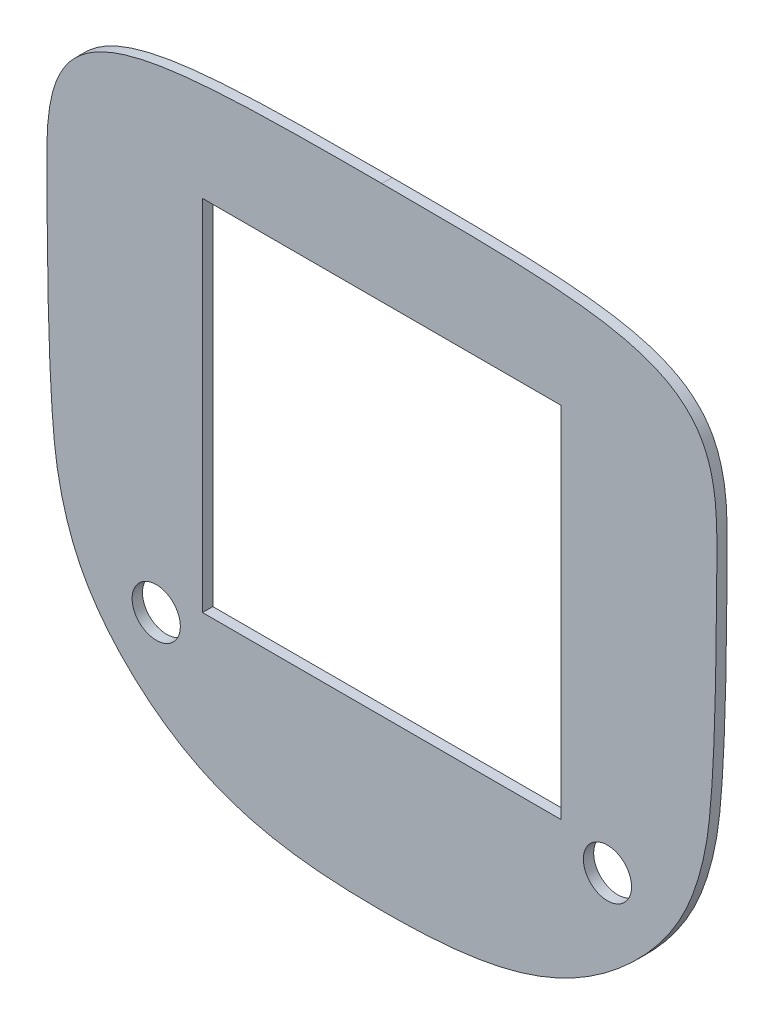
SolidWorks part; units mm, degrees
ref_plane "Front Plane" through (0, 0, 0) normal (0, 0, 1) x (1, 0, 0)
ref_plane "Top Plane" through (0, 0, 0) normal (0, 1, 0) x (1, 0, 0)
ref_plane "Right Plane" through (0, 0, 0) normal (1, 0, 0) x (0, 0, -1)
ref_plane "Plane1" through (0, 0, 100) normal (0, 0, -1) x (-1, 0, 0)
sketch "Sketch1" plane through (0, 0, 100) normal (0, 0, -1) x (-1, 0, 0)
  line L0 (0, 109.7056) -> (0, -73.1371) construction
  line L2 (-52.07, 79.9412) -> (52.07, 79.9412)
  line L3 (-52.07, 79.9412) -> (-52.07, -24.1988)
  line L4 (-52.07, -24.1988) -> (52.07, -24.1988)
  line L5 (52.07, 79.9412) -> (52.07, -24.1988)
  line L6 (-52.07, 79.9412) -> (52.07, -24.1988) construction
  line L7 (-52.07, -24.1988) -> (52.07, 79.9412) construction
  circle A0 centre (-65.5, -30.8878) radius 7
  circle A1 centre (65.5, -30.8878) radius 7
  spline S0 degree 3 poles (189.9332, -2044.6296) (318.3511, 79.8937) (143.1669, -78.9969) (-13.4407, -72.8192) (-16.7834, -72.6088) (-23.4392, -71.9641) (-26.7521, -71.5296) (-33.3376, -70.3562) (-36.61, -69.6165) (-40.6674, -68.4431) (-41.4772, -68.196) (-43.0934, -67.6755) (-43.9008, -67.4017) (-46.31, -66.5418) (-47.8892, -65.9204) (-52.5445, -63.9094) (-55.537, -62.3708) (-61.3063, -58.9085) (-64.0845, -56.9872) (-67.4275, -54.3545) (-68.0901, -53.8159) (-69.3935, -52.723) (-70.0355, -52.1678) (-71.9328, -50.4771) (-73.1598, -49.3164) (-76.728, -45.7341) (-78.9589, -43.2145) (-82.0396, -39.1995) (-83.0214, -37.8212) (-84.8841, -34.9749) (-85.7674, -33.501) (-88.2046, -29.0237) (-89.5634, -25.9428) (-91.2398, -21.1907) (-91.7446, -19.5872) (-92.6604, -16.3463) (-93.0697, -14.7082) (-93.7952, -11.3985) (-94.1118, -9.723) (-94.6517, -6.3658) (-94.8768, -4.683) (-95.2393, -1.3093) (-95.3906, 0.3804) (-95.6676, 3.7621) (-95.7898, 5.4545) (-96.0069, 8.8417) (-96.1016, 10.5367) (-96.2755, 13.928) (-96.3542, 15.6244) (-96.5678, 20.7138) (-96.6807, 24.1076) (-96.9534, 34.291) (-97.0459, 41.0827) (-97.1493, 51.27) (-97.1785, 54.6658) (-97.2277, 59.7595) (-97.2458, 61.4574) (-97.2868, 64.8533) (-97.3103, 66.5515) (-97.2904, 69.9429) (-97.2559, 71.6367) (-97.0958, 75.0177) (-96.9726, 76.705) (-96.5853, 80.0691) (-96.3204, 81.7458) (-95.8548, 83.8317) (-95.7548, 84.2484) (-95.5396, 85.0806) (-95.4241, 85.4969) (-95.0548, 86.7335) (-94.7779, 87.544) (-93.8439, 89.9287) (-93.0837, 91.4561) (-91.9173, 93.2675) (-91.6726, 93.6258) (-91.167, 94.3236) (-90.9058, 94.6639) (-90.0972, 95.6599) (-89.5251, 96.2905) (-88.3172, 97.4873) (-87.6813, 98.0535) (-86.6823, 98.8572) (-86.3418, 99.1176) (-85.6463, 99.6235) (-85.2903, 99.8697) (-83.4921, 101.0547) (-81.9897, 101.864) (-78.8918, 103.2801) (-77.2954, 103.8853) (-74.8499, 104.6822) (-74.0257, 104.9295) (-72.3778, 105.3877) (-71.5521, 105.5993) (-69.0705, 106.1898) (-67.4103, 106.5251) (-64.0815, 107.1133) (-62.4129, 107.3654) (-57.3979, 108.0286) (-54.0423, 108.3496) (-47.3172, 108.8523) (-43.9476, 109.0331) (-37.2, 109.3116) (-33.822, 109.4086) (-27.0609, 109.5527) (-23.6778, 109.5995) (217.6794, 111.91) (456.0514, 45.1883) (683.106, 1944.8895) knots -1.39702 -1.39702 -1.39702 -1.39702 0.03125 0.03125 0.0625 0.0625 0.09375 0.09375 0.125 0.125 0.132812 0.132812 0.140625 0.140625 0.15625 0.15625 0.1875 0.1875 0.21875 0.21875 0.226562 0.226562 0.234375 0.234375 0.25 0.25 0.28125 0.28125 0.296875 0.296875 0.3125 0.3125 0.34375 0.34375 0.359375 0.359375 0.375 0.375 0.390625 0.390625 0.40625 0.40625 0.421875 0.421875 0.4375 0.4375 0.453125 0.453125 0.46875 0.46875 0.5 0.5 0.5625 0.5625 0.59375 0.59375 0.609375 0.609375 0.625 0.625 0.640625 0.640625 0.65625 0.65625 0.671875 0.671875 0.675781 0.675781 0.679688 0.679688 0.6875 0.6875 0.703125 0.703125 0.707031 0.707031 0.710938 0.710938 0.71875 0.71875 0.726563 0.726563 0.730469 0.730469 0.734375 0.734375 0.75 0.75 0.765625 0.765625 0.773438 0.773438 0.78125 0.78125 0.796875 0.796875 0.8125 0.8125 0.84375 0.84375 0.875 0.875 0.90625 0.90625 0.9375 0.9375 3.136121 3.136121 3.136121 3.136121 only from (0, -73.1371) to (0, 109.7056)
  spline S1 degree 3 poles (0, -73.1371) (-3.3707, -73.1371) (-6.7344, -73.0838) (-13.4407, -72.8192) (-16.7834, -72.6088) (-23.4392, -71.9641) (-26.7521, -71.5296) (-33.3376, -70.3562) (-36.61, -69.6165) (-40.6674, -68.4431) (-41.4772, -68.196) (-43.0934, -67.6755) (-43.9008, -67.4017) (-46.31, -66.5418) (-47.8892, -65.9204) (-52.5445, -63.9094) (-55.537, -62.3708) (-61.3063, -58.9085) (-64.0845, -56.9872) (-67.4275, -54.3545) (-68.0901, -53.8159) (-69.3935, -52.723) (-70.0355, -52.1678) (-71.9328, -50.4771) (-73.1598, -49.3164) (-76.728, -45.7341) (-78.9589, -43.2145) (-82.0396, -39.1995) (-83.0214, -37.8212) (-84.8841, -34.9749) (-85.7674, -33.501) (-88.2046, -29.0237) (-89.5634, -25.9428) (-91.2398, -21.1907) (-91.7446, -19.5872) (-92.6604, -16.3463) (-93.0697, -14.7082) (-93.7952, -11.3985) (-94.1118, -9.723) (-94.6517, -6.3658) (-94.8768, -4.683) (-95.2393, -1.3093) (-95.3906, 0.3804) (-95.6676, 3.7621) (-95.7898, 5.4545) (-96.0069, 8.8417) (-96.1016, 10.5367) (-96.2755, 13.928) (-96.3542, 15.6244) (-96.5678, 20.7138) (-96.6807, 24.1076) (-96.9534, 34.291) (-97.0459, 41.0827) (-97.1493, 51.27) (-97.1785, 54.6658) (-97.2277, 59.7595) (-97.2458, 61.4574) (-97.2868, 64.8533) (-97.3103, 66.5515) (-97.2904, 69.9429) (-97.2559, 71.6367) (-97.0958, 75.0177) (-96.9726, 76.705) (-96.5853, 80.0691) (-96.3204, 81.7458) (-95.8548, 83.8317) (-95.7548, 84.2484) (-95.5396, 85.0806) (-95.4241, 85.4969) (-95.0548, 86.7335) (-94.7779, 87.544) (-93.8439, 89.9287) (-93.0837, 91.4561) (-91.9173, 93.2675) (-91.6726, 93.6258) (-91.167, 94.3236) (-90.9058, 94.6639) (-90.0972, 95.6599) (-89.5251, 96.2905) (-88.3172, 97.4873) (-87.6813, 98.0535) (-86.6823, 98.8572) (-86.3418, 99.1176) (-85.6463, 99.6235) (-85.2903, 99.8697) (-83.4921, 101.0547) (-81.9897, 101.864) (-78.8918, 103.2801) (-77.2954, 103.8853) (-74.8499, 104.6822) (-74.0257, 104.9295) (-72.3778, 105.3877) (-71.5521, 105.5993) (-69.0705, 106.1898) (-67.4103, 106.5251) (-64.0815, 107.1133) (-62.4129, 107.3654) (-57.3979, 108.0286) (-54.0423, 108.3496) (-47.3172, 108.8523) (-43.9476, 109.0331) (-37.2, 109.3116) (-33.822, 109.4086) (-27.0609, 109.5527) (-23.6778, 109.5995) (-13.5305, 109.6966) (-6.7653, 109.7056) (0, 109.7056) knots 0 0 0 0 0.03125 0.03125 0.0625 0.0625 0.09375 0.09375 0.125 0.125 0.132812 0.132812 0.140625 0.140625 0.15625 0.15625 0.1875 0.1875 0.21875 0.21875 0.226562 0.226562 0.234375 0.234375 0.25 0.25 0.28125 0.28125 0.296875 0.296875 0.3125 0.3125 0.34375 0.34375 0.359375 0.359375 0.375 0.375 0.390625 0.390625 0.40625 0.40625 0.421875 0.421875 0.4375 0.4375 0.453125 0.453125 0.46875 0.46875 0.5 0.5 0.5625 0.5625 0.59375 0.59375 0.609375 0.609375 0.625 0.625 0.640625 0.640625 0.65625 0.65625 0.671875 0.671875 0.675781 0.675781 0.679688 0.679688 0.6875 0.6875 0.703125 0.703125 0.707031 0.707031 0.710938 0.710938 0.71875 0.71875 0.726563 0.726563 0.730469 0.730469 0.734375 0.734375 0.75 0.75 0.765625 0.765625 0.773438 0.773438 0.78125 0.78125 0.796875 0.796875 0.8125 0.8125 0.84375 0.84375 0.875 0.875 0.90625 0.90625 0.9375 0.9375 1 1 1 1
  spline S2 degree 3 poles (0, -73.1371) (3.3707, -73.1371) (6.7344, -73.0838) (13.4407, -72.8192) (16.7834, -72.6088) (23.4392, -71.9641) (26.7521, -71.5296) (33.3376, -70.3562) (36.61, -69.6165) (40.6674, -68.4431) (41.4772, -68.196) (43.0934, -67.6755) (43.9008, -67.4017) (46.31, -66.5418) (47.8892, -65.9204) (52.5445, -63.9094) (55.537, -62.3708) (61.3063, -58.9085) (64.0845, -56.9872) (67.4275, -54.3545) (68.0901, -53.8159) (69.3935, -52.723) (70.0355, -52.1678) (71.9328, -50.4771) (73.1598, -49.3164) (76.728, -45.7341) (78.9589, -43.2145) (82.0396, -39.1995) (83.0214, -37.8212) (84.8841, -34.9749) (85.7674, -33.501) (88.2046, -29.0237) (89.5634, -25.9428) (91.2398, -21.1907) (91.7446, -19.5872) (92.6604, -16.3463) (93.0697, -14.7082) (93.7952, -11.3985) (94.1118, -9.723) (94.6517, -6.3658) (94.8768, -4.683) (95.2393, -1.3093) (95.3906, 0.3804) (95.6676, 3.7621) (95.7898, 5.4545) (96.0069, 8.8417) (96.1016, 10.5367) (96.2755, 13.928) (96.3542, 15.6244) (96.5678, 20.7138) (96.6807, 24.1076) (96.9534, 34.291) (97.0459, 41.0827) (97.1493, 51.27) (97.1785, 54.6658) (97.2277, 59.7595) (97.2458, 61.4574) (97.2868, 64.8533) (97.3103, 66.5515) (97.2904, 69.9429) (97.2559, 71.6367) (97.0958, 75.0177) (96.9726, 76.705) (96.5853, 80.0691) (96.3204, 81.7458) (95.8548, 83.8317) (95.7548, 84.2484) (95.5396, 85.0806) (95.4241, 85.4969) (95.0548, 86.7335) (94.7779, 87.544) (93.8439, 89.9287) (93.0837, 91.4561) (91.9173, 93.2675) (91.6726, 93.6258) (91.167, 94.3236) (90.9058, 94.6639) (90.0972, 95.6599) (89.5251, 96.2905) (88.3172, 97.4873) (87.6813, 98.0535) (86.6823, 98.8572) (86.3418, 99.1176) (85.6463, 99.6235) (85.2903, 99.8697) (83.4921, 101.0547) (81.9897, 101.864) (78.8918, 103.2801) (77.2954, 103.8853) (74.8499, 104.6822) (74.0257, 104.9295) (72.3778, 105.3877) (71.5521, 105.5993) (69.0705, 106.1898) (67.4103, 106.5251) (64.0815, 107.1133) (62.4129, 107.3654) (57.3979, 108.0286) (54.0423, 108.3496) (47.3172, 108.8523) (43.9476, 109.0331) (37.2, 109.3116) (33.822, 109.4086) (27.0609, 109.5527) (23.6778, 109.5995) (13.5305, 109.6966) (6.7653, 109.7056) (0, 109.7056) knots 0 0 0 0 0.03125 0.03125 0.0625 0.0625 0.09375 0.09375 0.125 0.125 0.132812 0.132812 0.140625 0.140625 0.15625 0.15625 0.1875 0.1875 0.21875 0.21875 0.226562 0.226562 0.234375 0.234375 0.25 0.25 0.28125 0.28125 0.296875 0.296875 0.3125 0.3125 0.34375 0.34375 0.359375 0.359375 0.375 0.375 0.390625 0.390625 0.40625 0.40625 0.421875 0.421875 0.4375 0.4375 0.453125 0.453125 0.46875 0.46875 0.5 0.5 0.5625 0.5625 0.59375 0.59375 0.609375 0.609375 0.625 0.625 0.640625 0.640625 0.65625 0.65625 0.671875 0.671875 0.675781 0.675781 0.679688 0.679688 0.6875 0.6875 0.703125 0.703125 0.707031 0.707031 0.710938 0.710938 0.71875 0.71875 0.726563 0.726563 0.730469 0.730469 0.734375 0.734375 0.75 0.75 0.765625 0.765625 0.773438 0.773438 0.78125 0.78125 0.796875 0.796875 0.8125 0.8125 0.84375 0.84375 0.875 0.875 0.90625 0.90625 0.9375 0.9375 1 1 1 1
  point P7 (0, 27.8712)
  point P12 (0, 0)
  point P13 (0, 0)
  point P14 (0, 0)
  point P15 (0, 0)
  dimension "D1" = 14
extrude "Boss-Extrude1" add sketch "Sketch1" along normal blind 3
